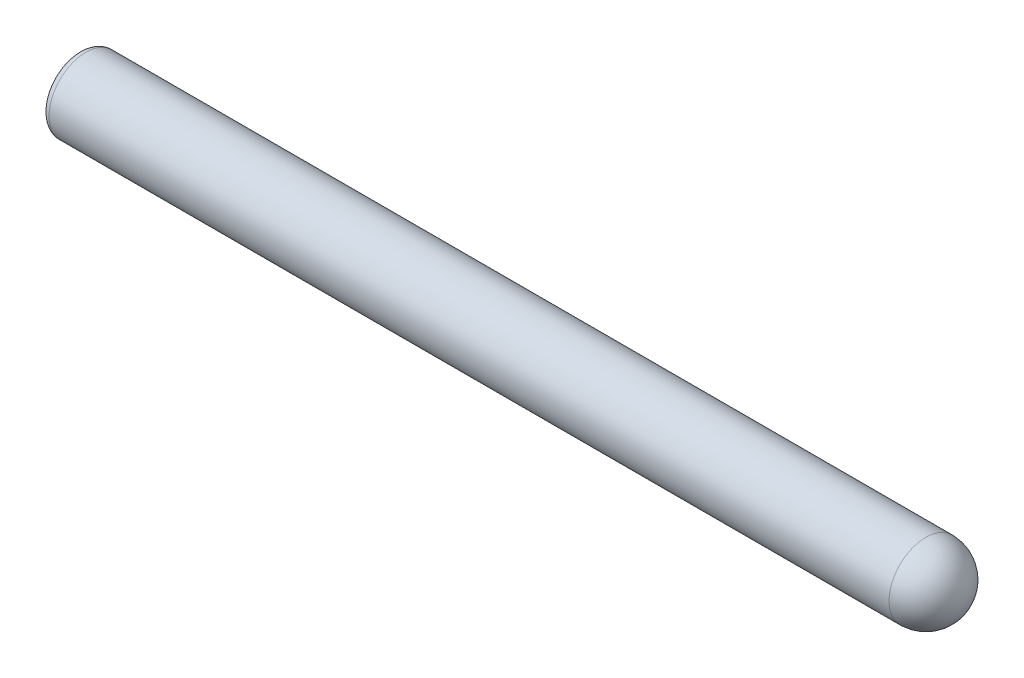
SolidWorks part; units mm, degrees
ref_plane "Plano frontal" through (0, 0, 0) normal (0, 0, 1) x (1, 0, 0)
ref_plane "Plano superior" through (0, 0, 0) normal (0, 1, 0) x (1, 0, 0)
ref_plane "Plano direito" through (0, 0, 0) normal (1, 0, 0) x (0, 0, -1)
sketch "Esboço1" plane through (0, 0, 0) normal (1, 0, 0) x (0, 0, -1)
  circle A0 centre (0, 0) radius 0.5
  dimension "D1" = 1
extrude "Ressalto-extrusão1" add sketch "Esboço1" along normal blind 12
fillet "Filete5" radius 0.5 1 edges at (12, 0, -0.5)
fillet "Filete6" radius 0.1 1 edges at (0, 0, -0.5)
